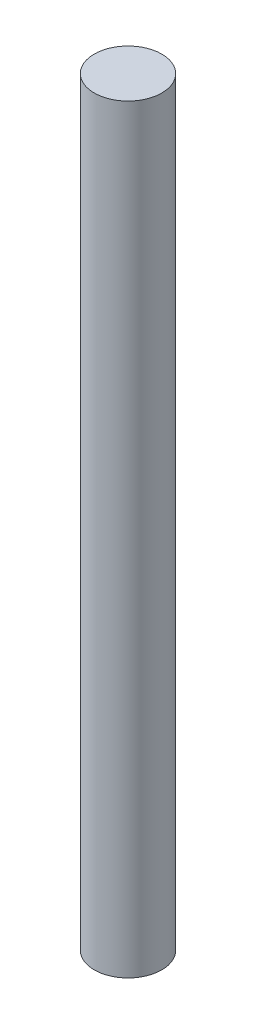
SolidWorks part; units mm, degrees
ref_plane "Front Plane" through (0, 0, 0) normal (0, 0, 1) x (1, 0, 0)
ref_plane "Top Plane" through (0, 0, 0) normal (0, 1, 0) x (1, 0, 0)
ref_plane "Right Plane" through (0, 0, 0) normal (1, 0, 0) x (0, 0, -1)
other "Configuration Table"
sketch "草图1" plane through (0, 0, 0) normal (0, 1, 0) x (1, 0, 0)
  circle A0 centre (0, 0) radius 2
  dimension "D1" = 4
extrude "凸台-拉伸1" add sketch "草图1" along normal blind 45
